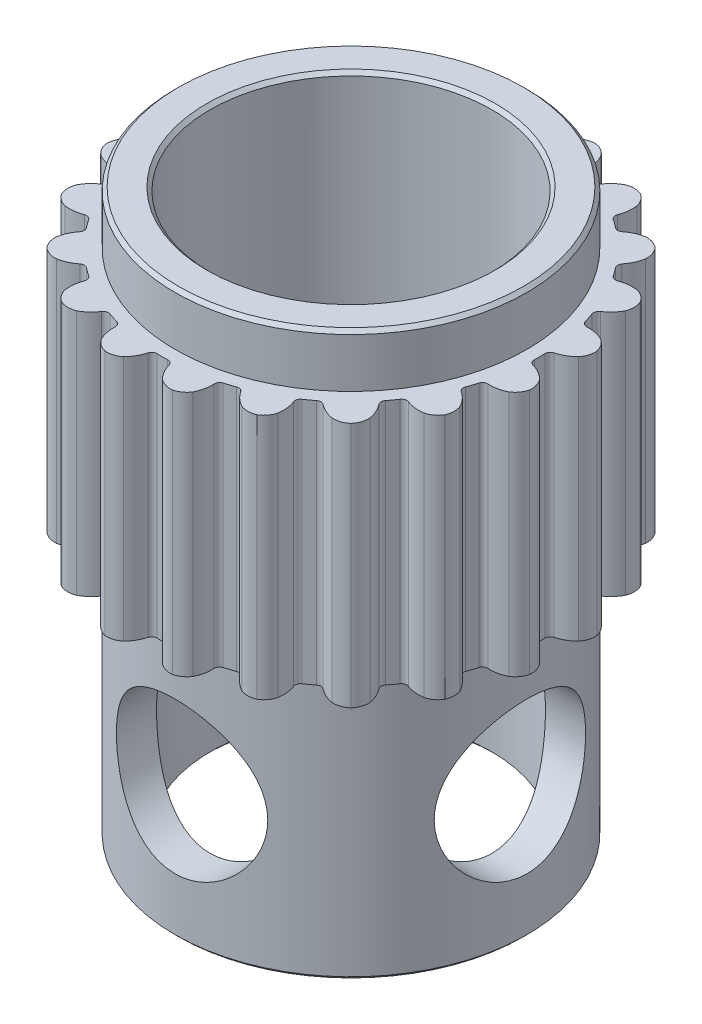
SolidWorks part; units mm, degrees
material "6061-T6 (SS)"
ref_plane "Front Plane" through (0, 0, 0) normal (0, 0, 1) x (1, 0, 0)
ref_plane "Top Plane" through (0, 0, 0) normal (0, 1, 0) x (1, 0, 0)
ref_plane "Right Plane" through (0, 0, 0) normal (1, 0, 0) x (0, 0, -1)
sketch "Body Sketch" plane through (0, 0, 0) normal (0, 0, 1) x (1, 0, 0)
  line L0 (6.11, -3.5) -> (6.11, 3.5)
  line L3 (6.11, 3.5) -> (4, 3.5)
  line L4 (4, 3.5) -> (4, -3.5)
  line L9 (4, -3.5) -> (6.11, -3.5)
  line L12 (0, 0) -> (6.11, 0) construction
  line L13 (0, 3.5) -> (0, -3.5) construction
  dimension "BoreDia" = 8
  dimension "Height" = 7
  dimension "RefBeltPathDia" = 12.22
revolve "Body" add sketch "Body Sketch" angle 360 about L13
sketch "GT2 Profile Sketch" plane through (0, 0, 0) normal (0, 1, 0) x (1, 0, 0)
  line L1 (0, -6.11) -> (0, -5.36) construction
  line L2 (-0.9955, -6.0283) -> (-0.8733, -5.2884) construction
  line L3 (0, 0) -> (-0.8733, -5.2884) construction
  line L4 (0.9955, -6.0283) -> (0, 0) construction
  arc A3 (0.2997, -5.4688) -> (0.1507, -5.3579) centre (0.1549, -5.5078) ccw
  arc A4 (-0.9955, -6.0283) -> (0.9955, -6.0283) centre (0, 0) ccw
  arc A5 (-0.2997, -5.4688) -> (-0.1507, -5.3579) centre (-0.1549, -5.5078) cw
  arc A6 (-0.2997, -5.4688) -> (-0.5497, -5.907) centre (-1.2653, -5.2085) cw
  arc A8 (-0.1507, -5.3579) -> (0.1507, -5.3579) centre (0, 0) ccw
  arc A9 (-0.5497, -5.907) -> (-0.9955, -6.0283) centre (-0.9051, -5.4808) cw
  arc A10 (0.2997, -5.4688) -> (0.5497, -5.907) centre (1.2653, -5.2085) ccw
  arc A11 (0.5497, -5.907) -> (0.9955, -6.0283) centre (0.9051, -5.4808) ccw
  circle A12 centre (0, 0) radius 5.36 construction
  circle A13 centre (0, 0) radius 6.11 construction
  dimension "BottomRadius" = 0.15
  dimension "MidRadius" = 1
  dimension "TopRadius" = 0.555
  dimension "Height" = 0.75
  dimension "XDistMidRadius" = 0.4
  dimension "ArcLengthAngle" = 18.755
  dimension "ArcLength" = 2
extrude "GT2 Profile" cut sketch "GT2 Profile Sketch" along direction (0, -1, 0) on the side against the normal up to next (3.5 mm away) and the other way up to next (3.5 mm away)
pattern_circular "GT2 Circular Pattern" count 20 over 360 about axis through (0, 0, 0) along (0, 1, 0) of "GT2 Profile"
sketch "Top Wall Sketch" plane through (0, 3.5, 0) normal (0, 1, 0) x (1, 0, 0)
  circle A0 centre (0, 0) radius 4 construction
  circle A1 centre (0, 0) radius 4
  circle A2 centre (0, 0) radius 5
  dimension "Thickness" = 1
extrude "Top Wall" add sketch "Top Wall Sketch" along normal blind 1.5
sketch "BottomWallS" plane through (0, -3.5, 0) normal (0, -1, 0) x (-1, 0, 0)
  circle A0 centre (0, 0) radius 4
  circle A1 centre (0, 0) radius 4 construction
  circle A2 centre (0, 0) radius 5
  circle A3 centre (0, 0) radius 5 construction
extrude "Bottom Wall" add sketch "BottomWallS" along normal blind 7.5
ref_plane "Clearance Hole Plane" through (0, 0, 5) normal (0, 0, 1) x (1, 0, 0)
hole_wizard "Set Screw Clearance Hole" positions "Sketch1" profile "Sketch2" hole size "M4" standard "ANSI Metric"
sketch "Sketch1" plane through (0, 0, 5) normal (0, 0, 1) x (1, 0, 0)
  line L0 (0, -11) -> (0, -3.5) construction
  line L1 (-5, -11) -> (5, -11) construction
  line L2 (-0.1507, -3.5) -> (0.1507, -3.5) construction
  point P0 (0, -7.25)
sketch "Sketch2" plane through (0, -7.25, 5) normal (1, 0, 0) x (0, -1, 0)
  line L0 (0, 0) -> (0, 1)
  line L1 (0, 1) -> (2.15, 1)
  line L2 (2.15, 1) -> (2.15, 0)
  line L5 (2.15, 0) -> (0, 0)
  line L11 (0, -6.35) -> (0, 107.95) construction
  dimension "Thru Hole Dia." = 4.3
  dimension "Thru Hole Depth" = 1
pattern_circular "Set Screw Hole Pattern" count 2 every 90 about axis through (0, -11, 0) along (0, 1, 0) of "Set Screw Clearance Hole"
chamfer "Inner Chamfer" distance 0.1 angle 45 2 edges at (0, 5, 4) (0, -11, -4)
chamfer "Outer Chamfer" distance 0.1 angle 45 2 edges at (0, -11, -5) (0, 5, 5)
equation "\"D1@GT2 Circular Pattern\" = int ( 360 / \"ArcLengthAngle@GT2 Profile Sketch\" )  + 1"
